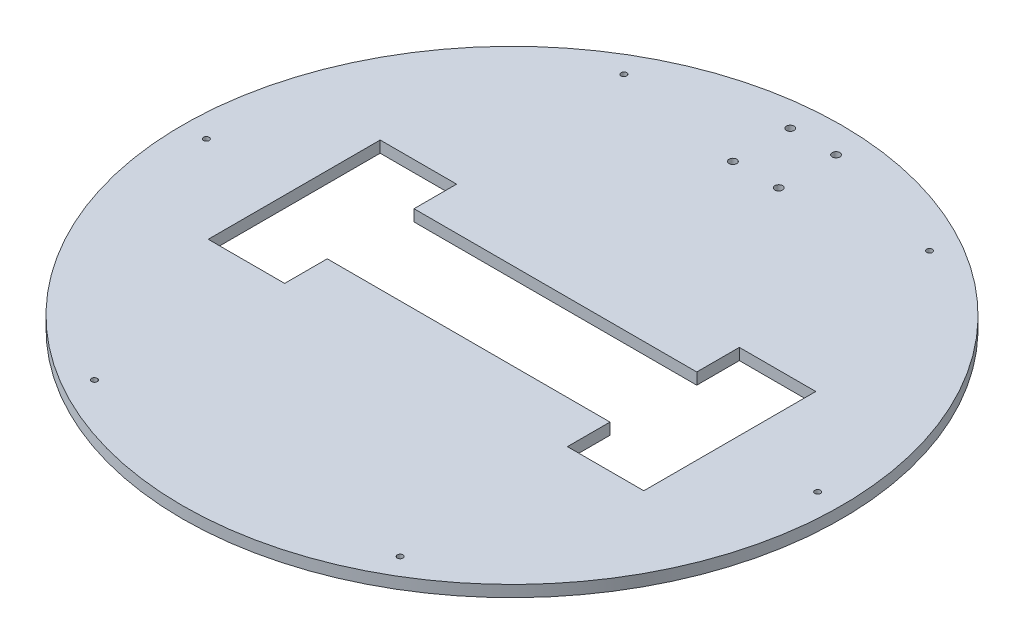
SolidWorks part; units mm, degrees
ref_plane "前视基准面" through (0, 0, 0) normal (0, 0, 1) x (1, 0, 0)
ref_plane "上视基准面" through (0, 0, 0) normal (0, 1, 0) x (1, 0, 0)
ref_plane "右视基准面" through (0, 0, 0) normal (1, 0, 0) x (0, 0, -1)
sketch "草图1" plane through (0, 0, 0) normal (0, 1, 0) x (1, 0, 0)
  line L0 (-172.5, 0) -> (172.5, 0)
  line L1 (0, -55) -> (0, 55) construction
  line L2 (-114, 45) -> (-74, 45)
  line L3 (-114, 45) -> (-114, -45)
  line L4 (-114, -45) -> (-74, -45)
  line L5 (-74, 45) -> (-74, -45)
  line L6 (-114, 45) -> (-74, -45) construction
  line L7 (-114, -45) -> (-74, 45) construction
  line L8 (114, -45) -> (74, -45)
  line L9 (114, 45) -> (74, 45)
  line L10 (114, 45) -> (114, -45)
  line L11 (74, 45) -> (74, -45)
  line L12 (0, 0) -> (0, 172.5) construction
  line L13 (-74, -22.7059) -> (74, -22.7059)
  line L14 (-74, -22.7059) -> (-74, 22.7059)
  line L15 (-74, 22.7059) -> (74, 22.7059)
  line L16 (74, -22.7059) -> (74, 22.7059)
  line L17 (-74, -22.7059) -> (74, 22.7059) construction
  line L18 (-74, 22.7059) -> (74, -22.7059) construction
  line L19 (12, 157.6204) -> (-12, 157.6204) construction
  line L20 (12, 157.6204) -> (12, 127.6204) construction
  line L21 (12, 127.6204) -> (-12, 127.6204) construction
  line L22 (-12, 157.6204) -> (-12, 127.6204) construction
  line L23 (12, 157.6204) -> (-12, 127.6204) construction
  line L24 (12, 127.6204) -> (-12, 157.6204) construction
  circle A0 centre (0, 0) radius 172.5
  circle A3 centre (12, 157.6204) radius 2.013
  circle A4 centre (-12, 157.6204) radius 2.013
  circle A5 centre (-12, 127.6204) radius 2.013
  circle A6 centre (12, 127.6204) radius 2.013
  circle A7 centre (-160, 0) radius 1.5
  circle A8 centre (-80, 138.5641) radius 1.5
  circle A9 centre (80, 138.5641) radius 1.5
  circle A10 centre (160, 0) radius 1.5
  circle A11 centre (80, -138.5641) radius 1.5
  circle A12 centre (-80, -138.5641) radius 1.5
  point P5 (-94, 0)
  point P20 (0, 142.6204)
  dimension "D1" = 6
extrude "凸台-拉伸2" add sketch "草图1" against normal blind 6
